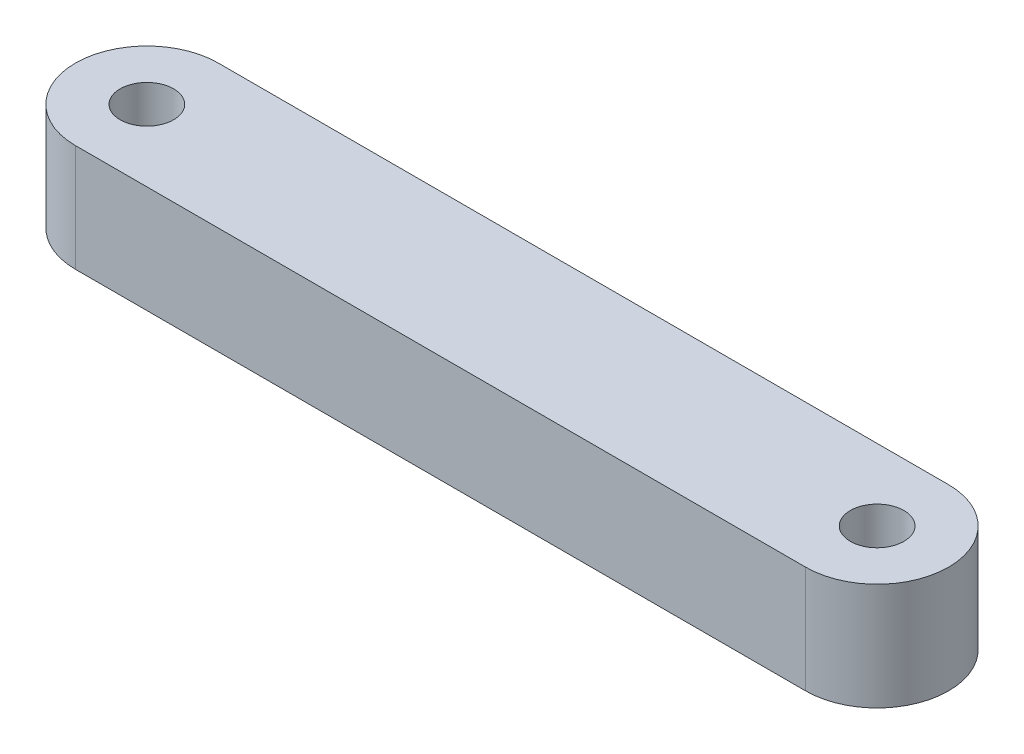
SolidWorks part; units mm, degrees
ref_plane "Front Plane" through (0, 0, 0) normal (0, 0, 1) x (1, 0, 0)
ref_plane "Top Plane" through (0, 0, 0) normal (0, 1, 0) x (1, 0, 0)
ref_plane "Right Plane" through (0, 0, 0) normal (1, 0, 0) x (0, 0, -1)
sketch "Sketch1" plane through (0, 0, 0) normal (0, 1, 0) x (1, 0, 0)
  line L0 (-10.22, 0) -> (10.22, 0) construction
  line L1 (-10.22, 2) -> (10.22, 2)
  line L2 (-10.22, -2) -> (10.22, -2)
  line L3 (0, -2.2) -> (0, 2.2) construction
  arc A0 (-10.22, 2) -> (-10.22, -2) centre (-10.22, 0) ccw
  arc A1 (10.22, -2) -> (10.22, 2) centre (10.22, 0) ccw
  circle A2 centre (-10.22, 0) radius 0.75
  circle A3 centre (10.22, 0) radius 0.75
  point P2 (0, 0)
  dimension "D2" = 2
  dimension "D3" = 1.5
  dimension "D1" = 20.44
extrude "Boss-Extrude1" add sketch "Sketch1" along normal blind 3
